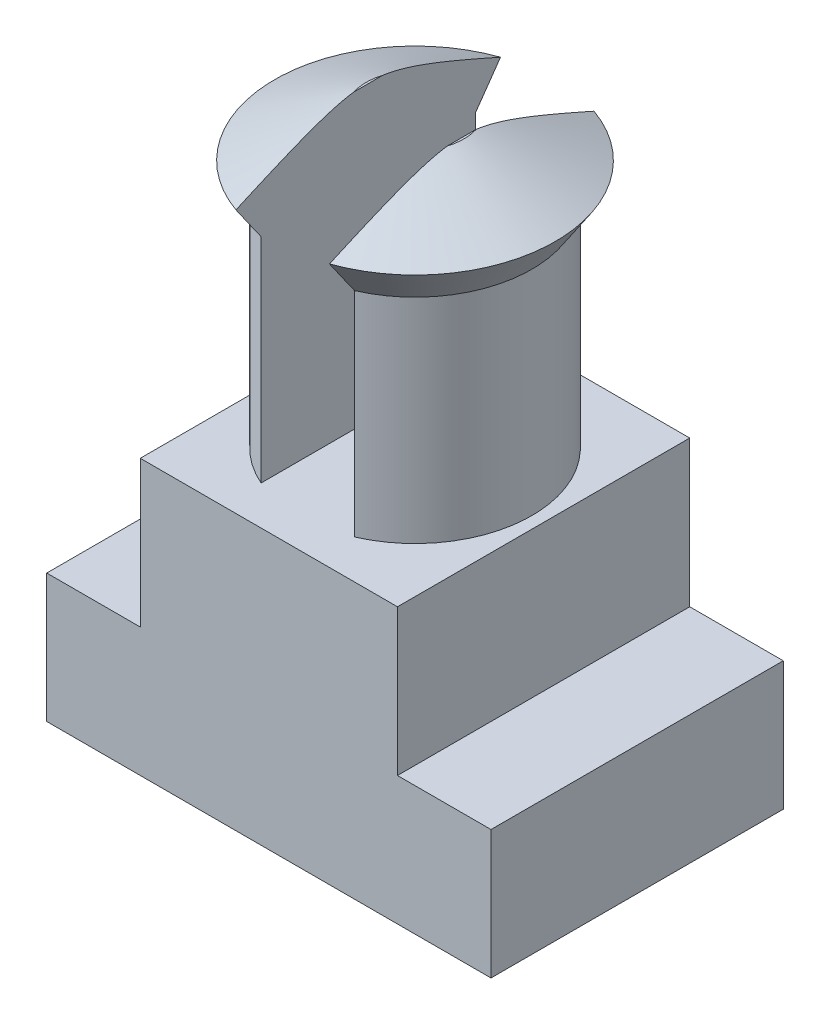
SolidWorks part; units mm, degrees
ref_plane "Front Plane" through (0, 0, 0) normal (0, 0, 1) x (1, 0, 0)
ref_plane "Top Plane" through (0, 0, 0) normal (0, 1, 0) x (1, 0, 0)
ref_plane "Right Plane" through (0, 0, 0) normal (1, 0, 0) x (0, 0, -1)
sketch "Sketch1" plane through (0, 0, 0) normal (0, 0, 1) x (1, 0, 0)
  line L0 (0, 0) -> (9.652, 0)
  line L1 (0, 0) -> (0, 2.794)
  line L2 (0, 2.794) -> (2.032, 2.794)
  line L3 (2.032, 2.794) -> (2.032, 5.969)
  line L4 (2.032, 5.969) -> (7.62, 5.969)
  line L5 (7.62, 5.969) -> (7.62, 2.794)
  line L6 (7.62, 2.794) -> (9.652, 2.794)
  line L7 (9.652, 2.794) -> (9.652, 0)
  point P3 (0, 0)
  dimension "D1" = 9.652
  dimension "D2" = 2.794
  dimension "D3" = 2.032
  dimension "D4" = 5.588
  dimension "D5" = 2.794
  dimension "D6" = 3.175
extrude "Boss-Extrude1" add sketch "Sketch1" along normal mid plane 6.35
sketch "Sketch2" plane through (0, 5.969, 0) normal (0, 1, 0) x (1, 0, 0)
  circle A0 centre (4.826, 0) radius 2.54
  point P2 (0, 0)
  dimension "D1" = 5.08
sketch "Sketch3" plane through (0, 0, 0) normal (0, 0, 1) x (1, 0, 0)
  line L0 (4.826, 5.969) -> (4.826, 15.7401) construction
  line L2 (3.7622, 12.319) -> (4.3265, 12.319)
  line L3 (4.3265, 12.319) -> (4.3265, 5.969)
  line L4 (7.366, 5.969) -> (2.286, 5.969) construction
  line L5 (4.3265, 5.969) -> (2.286, 5.969)
  line L6 (7.62, 5.969) -> (2.032, 5.969) construction
  line L7 (2.286, 5.969) -> (2.286, 10.6045)
  line L8 (2.286, 10.6045) -> (1.778, 11.3805)
  line L9 (1.778, 11.3805) -> (3.7622, 12.319)
  point P2 (1.778, 13.2209)
  point P6 (0, 0)
  point P15 (1.778, 11.1121)
  point P16 (1.778, 11.32)
  point P17 (0, 0)
  point P18 (1.778, 11.5765)
  point P19 (1.778, 11.3805)
  dimension "D1" = 6.35
  dimension "D2" = 4.6355
  dimension "D3" = 3.048
  dimension "D4" = 2.54
revolve "Revolve1" add sketch "Sketch3" angle 360 about L0
sketch "Sketch4" plane through (0, 0, 0) normal (0, 0, 1) x (1, 0, 0)
  line L0 (5.3255, 12.319) -> (4.3265, 12.319) construction
  line L1 (3.81, 18.669) -> (5.842, 18.669)
  line L2 (3.81, 18.669) -> (3.81, 5.969)
  line L3 (3.81, 5.969) -> (5.842, 5.969)
  line L4 (5.842, 18.669) -> (5.842, 5.969)
  line L5 (3.81, 18.669) -> (5.842, 5.969) construction
  line L6 (3.81, 5.969) -> (5.842, 18.669) construction
  line L7 (7.366, 5.969) -> (2.286, 5.969) construction
  point P0 (4.826, 12.319)
  dimension "D1" = 2.032
extrude "Cut-Extrude1" cut sketch "Sketch4" against normal through all both and the other way through all
